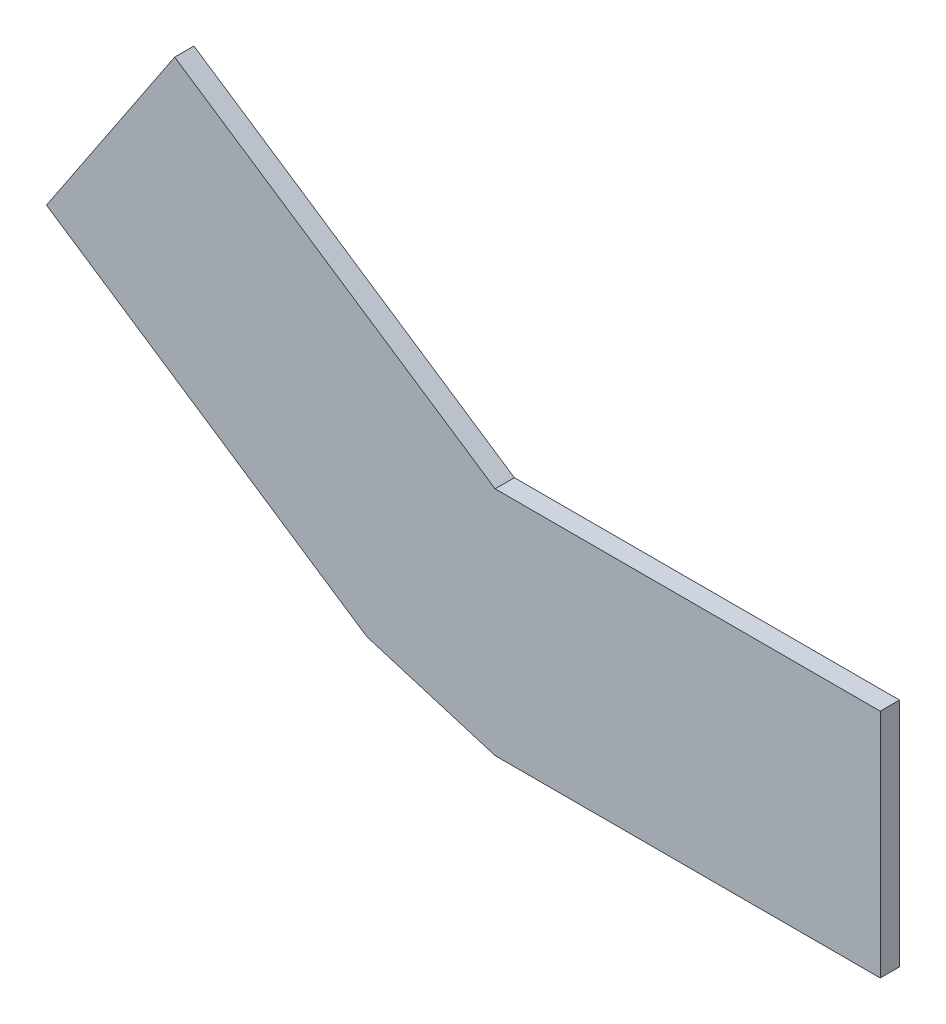
SolidWorks part; units mm, degrees
ref_plane "Front Plane" through (0, 0, 0) normal (0, 0, 1) x (1, 0, 0)
ref_plane "Top Plane" through (0, 0, 0) normal (0, 1, 0) x (1, 0, 0)
ref_plane "Right Plane" through (0, 0, 0) normal (1, 0, 0) x (0, 0, -1)
sketch "Sketch1" plane through (0, 0, 0) normal (0, 0, 1) x (1, 0, 0)
  line L0 (-304.5285, -3.2376) -> (-304.5285, -8.2376)
  line L5 (-304.5285, -3.2376) -> (-399.5285, -3.2376)
  line L10 (-304.5285, -8.2376) -> (-399.5285, -8.2376)
  line L12 (-495.2148, 55.2505) -> (-497.6755, 51.5595) construction
  line L21 (-495.2148, 55.2505) -> (-418.7859, 4.7922)
  line L24 (-482.7335, 80.6824) -> (-399.5285, 25.2124)
  line L26 (-432.8105, -24.7106) -> (-516.0155, 30.7594)
  line L27 (-516.0155, 30.7594) -> (-482.7335, 80.6824)
  line L28 (-399.5285, 25.2124) -> (-299.5285, 25.2124)
  line L29 (-299.5285, 25.2124) -> (-299.5285, -34.7876)
  line L30 (-299.5285, -34.7876) -> (-399.5285, -34.7876)
  line L32 (-432.8105, -24.7106) -> (-399.5285, -34.7876)
  line L33 (-482.7598, 73.7242) -> (-407.3472, 24.5425)
  line L34 (-482.7598, 73.7242) -> (-485.3956, 69.8379)
  line L37 (-397.5072, 19.5239) -> (-304.5285, 19.5239)
  line L38 (-304.5285, 17.2124) -> (-304.5285, 19.5239)
  line L41 (-397.5072, 14.7124) -> (-304.5285, 14.7124)
  line L42 (-304.5285, 17.2124) -> (-304.5285, 14.7124)
  line L44 (-485.3956, 69.8379) -> (-409.9974, 20.4929)
  line L48 (-418.7859, -1.0336) -> (-497.6755, 51.5595)
  line L49 (-497.6755, 51.5595) -> (-495.2148, 55.2505)
  line L50 (-304.5285, -13.3376) -> (-304.5285, -18.3376)
  line L51 (-304.5285, -13.3376) -> (-403.5899, -13.3376)
  line L52 (-403.5899, -13.3376) -> (-403.5899, -18.3376)
  line L53 (-403.5899, -18.3376) -> (-304.5285, -18.3376)
  line L54 (-501.0212, 46.541) -> (-503.7947, 42.3808)
  line L55 (-407.3472, 24.5425) -> (-409.9974, 20.4929)
  line L56 (-501.0212, 46.541) -> (-418.7859, -7.2785)
  line L58 (-418.7859, 4.7922) -> (-418.7859, -1.0336)
  line L59 (-503.7947, 42.3808) -> (-418.7859, -13.2543)
  line L62 (-501.0212, 46.541) -> (-503.7947, 42.3808) construction
  line L63 (-418.7859, -7.2785) -> (-418.7859, -13.2543)
  line L64 (-399.5285, -3.2376) -> (-399.5285, -8.2376)
  line L65 (-397.5072, 19.5239) -> (-397.5072, 14.7124)
  point P0 (-304.5285, -3.2376)
  dimension "D2" = 100
  dimension "D3" = 17.95
  dimension "D12" = 28.05
  dimension "D4" = 5
  dimension "D5" = 60
  dimension "D6" = 100
  dimension "D13" = 5
  dimension "D15" = 60
  dimension "D18" = 5
  dimension "D19" = 5
extrude "Boss-Extrude4" add sketch "Sketch1" along normal blind 5 contours L28 L29 L30 L32 L26 L27 L24
